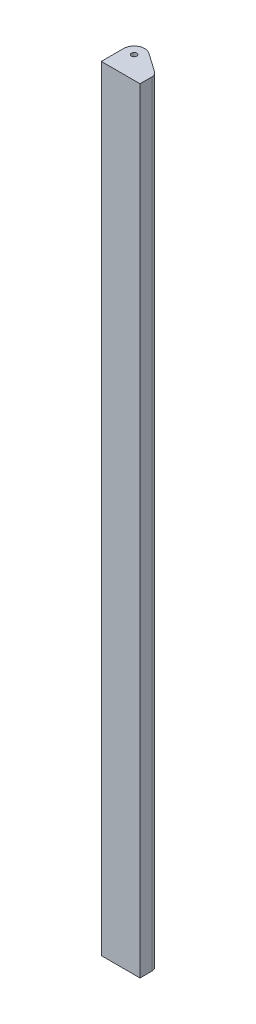
SolidWorks part; units mm, degrees
ref_plane "Front Plane" through (0, 0, 0) normal (0, 0, 1) x (1, 0, 0)
ref_plane "Top Plane" through (0, 0, 0) normal (0, 1, 0) x (1, 0, 0)
ref_plane "Right Plane" through (0, 0, 0) normal (1, 0, 0) x (0, 0, -1)
sketch "Sketch1" plane through (0, 0, 0) normal (0, 1, 0) x (1, 0, 0)
  line L0 (19.05, 63.5) -> (19.05, 0) construction
  line L5 (19.05, 0) -> (109.7374, 0)
  line L6 (64.4344, 31.7215) -> (29.9766, 55.8491)
  line L8 (0, 40.2442) -> (0, 0)
  line L10 (69.85, 21.3183) -> (69.85, 0)
  line L11 (19.05, 0) -> (0, 0)
  arc A1 (29.9766, 55.8491) -> (0, 40.2442) centre (19.05, 40.2442) ccw
  circle A2 centre (19.05, 40.2442) radius 4.7625
  arc A3 (29.9766, 55.8491) -> (0, 40.2442) centre (19.05, 40.2442) ccw
  arc A4 (69.85, 21.3183) -> (64.4344, 31.7215) centre (57.15, 21.3183) ccw
  dimension "D3" = 38.1
  dimension "D5" = 9.525
  dimension "D10" = 12.7
  dimension "D1" = 35
  dimension "D2" = 63.5
  dimension "D4" = 55.8491
  dimension "D6" = 90
  dimension "D7" = 19.05
  dimension "D8" = 40.2442
  dimension "D9" = 50.8
extrude "Boss-Extrude1" add sketch "Sketch1" along normal blind 1397 contours A1 L0 A2 L8 L5 L6 | L0 A3 L8 A2
